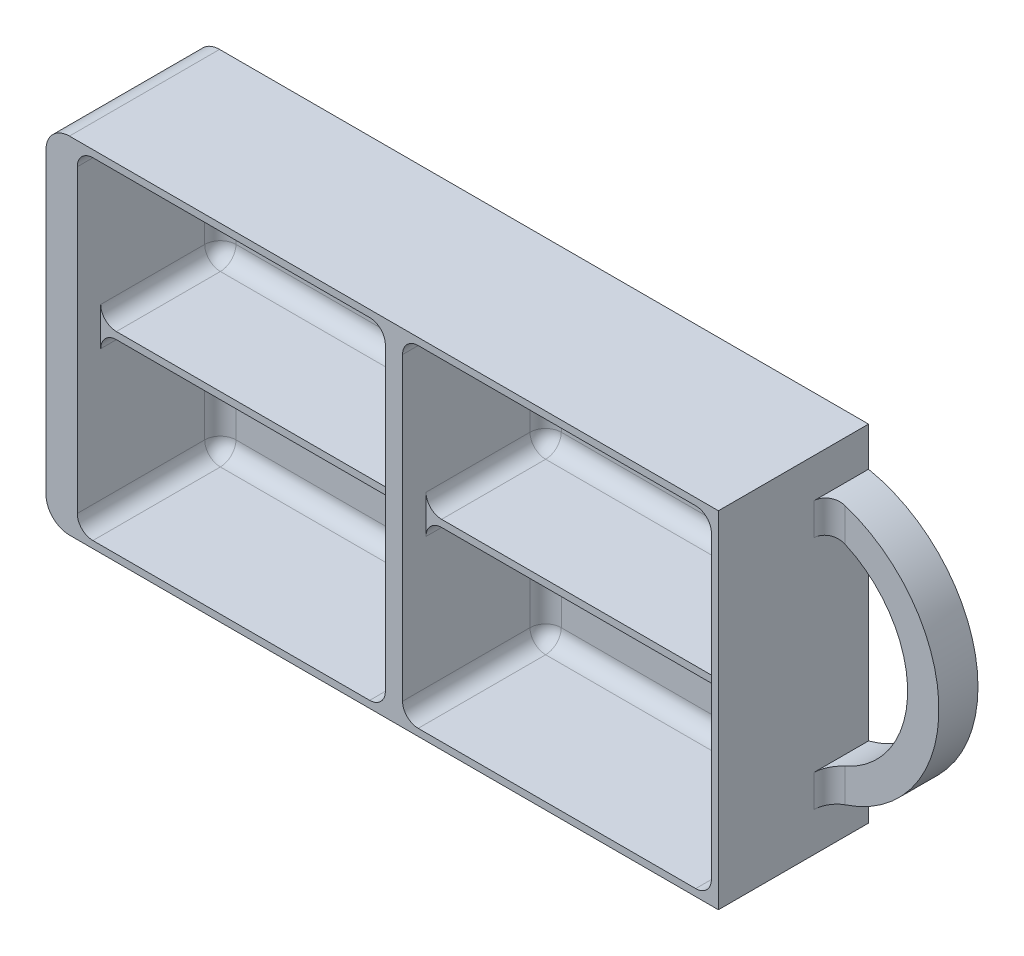
SolidWorks part; units mm, degrees
ref_plane "Спереди" through (0, 0, 0) normal (0, 0, 1) x (1, 0, 0)
ref_plane "Сверху" through (0, 0, 0) normal (0, 1, 0) x (1, 0, 0)
ref_plane "Справа" through (0, 0, 0) normal (1, 0, 0) x (0, 0, -1)
ref_plane "Плоскость4" through (0, 0, 9.6) normal (0, 0, 1) x (1, 0, 0)
sketch "Эскиз1" plane through (0, 0, 9.6) normal (0, 0, 1) x (1, 0, 0)
  line L0 (90, -22.1) -> (90, 22.1)
  line L1 (90, 22.1) -> (4, 22.1)
  line L2 (4, 22.1) -> (4, -22.1)
  line L3 (4, -22.1) -> (90, -22.1)
extrude "Бобышка-Вытянуть1" add sketch "Эскиз1" against normal blind 14.2
sketch "Эскиз2" plane through (0, 0, -4.6) normal (0, 0, -1) x (-1, 0, 0)
  line L0 (-90, -22.1) -> (-90, -17.1)
  line L1 (-90, 17.1) -> (-90, 22.1)
  line L2 (-90, 22.1) -> (-4, 22.1)
  line L3 (-4, 22.1) -> (-4, -22.1)
  line L4 (-4, -22.1) -> (-90, -22.1)
  line L5 (-90, -12.9948) -> (-90, 12.9948)
  arc A0 (-90, -17.1) -> (-90, 17.1) centre (-86.5568, 0) cw
  arc A1 (-90, 12.9948) -> (-90, -12.9948) centre (-86.5568, 0) ccw
extrude "Бобышка-Вытянуть2" add sketch "Эскиз2" along normal blind 5
sketch "Эскиз3" plane through (0, 0, 9.6) normal (0, 0, 1) x (1, 0, 0)
  line L0 (8, -21.2) -> (89.1, -21.2)
  line L1 (89.1, -21.2) -> (89.1, 21.2)
  line L2 (89.1, 21.2) -> (8, 21.2)
  line L3 (8, 21.2) -> (8, -21.2)
extrude "Вырез-Вытянуть1" cut sketch "Эскиз3" against normal blind 18.3
hole_wizard "Диаметр отверстия Ø8.3 (8.3)1" positions "Эскиз5" profile "Эскиз4" hole size "Ø8.3" standard "Ansi Metric"
sketch "Эскиз5" plane through (4, 0, 0) normal (-1, 0, 0) x (0, 0, 1)
  point P0 (0, 0)
sketch "Эскиз4" plane through (4, 0, 0) normal (0, 1, 0) x (0, 0, 1)
  line L0 (0, 0) -> (0, 3.2)
  line L1 (0, 3.2) -> (4.15, 3.2)
  line L2 (4.15, 3.2) -> (4.15, 0)
  line L5 (4.15, 0) -> (0, 0)
  line L10 (0, 3.2) -> (-4.15, 3.2) construction
  line L11 (0, -6.35) -> (0, 107.95) construction
  dimension "Диаметр отверстия" = 8.3
  dimension "Глубина отверстия" = 3.2
  dimension "Угол заточки сверла" = 180
sketch "Эскиз6" plane through (0, 0, 0) normal (0, 1, 0) x (1, 0, 0)
  line L0 (8, -6.6) -> (89.1, -6.6)
rib "Ребро1" sketch "Эскиз6" sketch "Эскиз6" thickness 0.9 extrusion direction parallel to sketch draft on no parameters "D1"=0.9
fillet "Скругление1" radius 3 2 edges at (4, -22.1, 0) (4, 22.1, 0)
sketch "Эскиз7" plane through (4, 0, 0) normal (-1, 0, 0) x (0, 0, 1)
  circle A0 centre (0, 0) radius 4.15 construction
  circle A1 centre (0, 0) radius 4.15
extrude "Бобышка-Вытянуть3" add sketch "Эскиз7" against normal blind 3.5
fillet "Скругление2" radius 2 18 edges at (90, 15.0474, -4.6) (90, -15.0474, -4.6) (8, -21.2, 0.45) (48.55, -21.2, -8.7) (89.1, -21.2, 0.45) (89.1, -10.825, -8.7) (89.1, -0.45, -1.05) (8, -10.825, -8.7) (8, -0.45, -1.05) (48.55, -0.45, -8.7) (89.1, 0.45, -1.05) (89.1, 21.2, 0.45) (89.1, 10.825, -8.7) (48.55, 0.45, -8.7) (8, 10.825, -8.7) (8, 0.45, -1.05) (8, 21.2, 0.45) (48.55, 21.2, -8.7)
sketch "Эскиз9" plane through (0, 22.1, 0) normal (0, 1, 0) x (1, 0, 0)
  line L1 (7, 9.6) -> (90, 9.6) construction
  line L2 (47.4, 9.6) -> (47.4, -9.6)
  line L3 (90, -9.6) -> (7, -9.6) construction
  line L4 (49.6, 9.6) -> (49.6, -9.6)
  line L5 (47.4, 9.6) -> (49.6, 9.6)
  line L6 (47.4, -9.6) -> (49.6, -9.6)
  dimension "D1" = 40.4
  dimension "D2" = 2.2
extrude "Бобышка-Вытянуть4" add sketch "Эскиз9" against normal blind 44
fillet "Скругление3" radius 2 20 edges at (47.4, -21.2, 1.45) (47.4, -20.6142, -8.1142) (47.4, -10.825, -8.7) (47.4, -1.0358, -8.1142) (47.4, 0.45, -0.05) (47.4, 1.0358, -8.1142) (47.4, 10.825, -8.7) (47.4, 20.6142, -8.1142) (49.6, -21.2, 1.45) (49.6, -20.6142, -8.1142) (49.6, -10.825, -8.7) (49.6, -1.0358, -8.1142) (49.6, 0.45, -0.05) (49.6, 1.0358, -8.1142) (49.6, 10.825, -8.7) (49.6, 20.6142, -8.1142) (47.4, -0.45, -0.05) (47.4, 21.2, 1.45) (49.6, -0.45, -0.05) (49.6, 21.2, 1.45)
